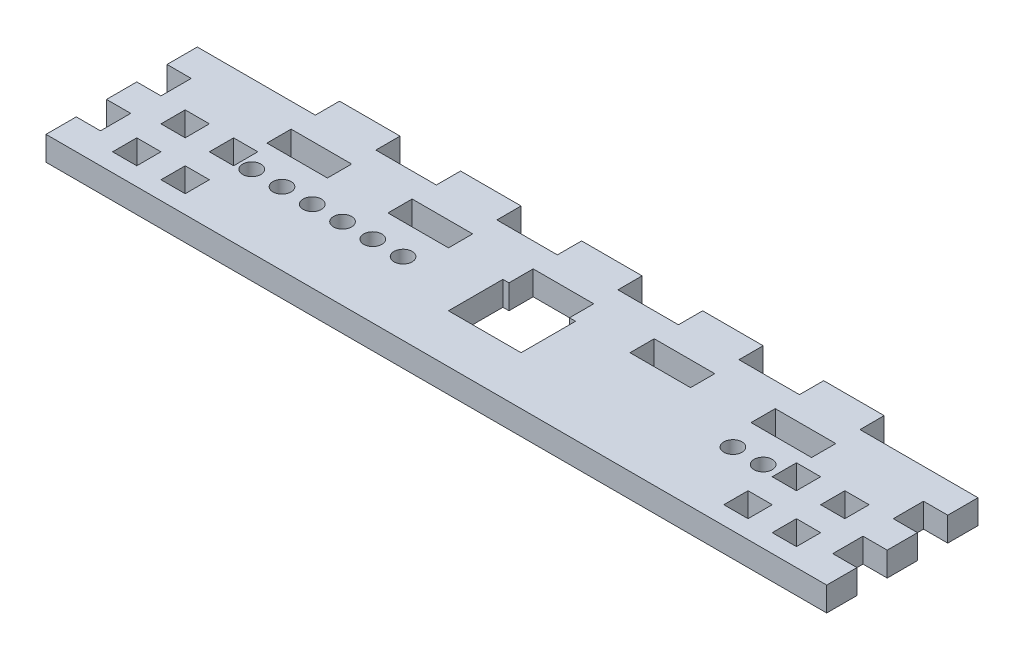
SolidWorks part; units mm, degrees
material "Maple"
ref_plane "Front Plane" through (0, 0, 0) normal (0, 0, 1) x (1, 0, 0)
ref_plane "Top Plane" through (0, 0, 0) normal (0, 1, 0) x (1, 0, 0)
ref_plane "Right Plane" through (0, 0, 0) normal (1, 0, 0) x (0, 0, -1)
sketch "Sketch1" plane through (0, 0, 0) normal (0, 1, 0) x (1, 0, 0)
  line L1 (0, 0) -> (121, 0)
  line L2 (0, 0) -> (0, -25)
  line L3 (0, -25) -> (121, -25)
  line L4 (121, 0) -> (121, -25)
  dimension "D1" = 121
  dimension "D2" = 25
extrude "Boss-Extrude1" add sketch "Sketch1" along normal blind 4
sketch "Sketch2" plane through (0, 0, 0) normal (0, -1, 0) x (-1, 0, 0)
  line L0 (0, 0) -> (0, -25) construction
  line L1 (0, -25) -> (4, -25)
  line L2 (0, -25) -> (0, -20)
  line L3 (0, -20) -> (4, -20)
  line L4 (4, -25) -> (4, -20)
  line L5 (-121, -25) -> (-125, -25)
  line L6 (-121, -25) -> (-121, -20)
  line L7 (-121, -20) -> (-125, -20)
  line L8 (-125, -25) -> (-125, -20)
  line L9 (0, -25) -> (-121, -25) construction
  dimension "D1" = 4
  dimension "D2" = 5
extrude "Boss-Extrude2" add sketch "Sketch2" against normal through all
pattern_linear "LPattern1" count 3 spacing 10 along (0, 0, -1) of "Boss-Extrude2"
sketch "Sketch3" plane through (0, 0, 0) normal (0, -1, 0) x (-1, 0, 0)
  line L0 (-60.5, -25) -> (-60.5, 0) construction
  line L1 (4, -25) -> (-125, -25) construction
  line L2 (-125, 0) -> (4, 0) construction
  line L4 (-55.5, 4) -> (-65.5, 4)
  line L5 (-55.5, 4) -> (-55.5, 0)
  line L6 (-55.5, 0) -> (-65.5, 0)
  line L7 (-65.5, 4) -> (-65.5, 0)
  line L8 (-55.5, 4) -> (-65.5, 0) construction
  line L9 (-55.5, 0) -> (-65.5, 4) construction
  point P6 (-60.5, 2)
  dimension "D1" = 4
  dimension "D2" = 10
extrude "Boss-Extrude3" add sketch "Sketch3" against normal through all
pattern_linear "LPattern2" count 3 spacing 20 along (1, 0, 0) count 3 spacing 20 along (-1, 0, 0) of "Boss-Extrude3"
sketch "Sketch4" plane through (0, 0, 0) normal (0, -1, 0) x (1, 0, 0)
  line L0 (60.5, -4) -> (60.5, 25) construction
  line L1 (15.5, 8) -> (25.5, 8)
  line L2 (15.5, 8) -> (15.5, 4)
  line L3 (15.5, 4) -> (25.5, 4)
  line L4 (25.5, 8) -> (25.5, 4)
  line L5 (35.5, 8) -> (45.5, 8)
  line L6 (35.5, 8) -> (35.5, 4)
  line L7 (35.5, 4) -> (45.5, 4)
  line L8 (45.5, 8) -> (45.5, 4)
  line L9 (55.5, 8) -> (65.5, 8)
  line L10 (55.5, 8) -> (55.5, 4)
  line L11 (55.5, 4) -> (65.5, 4)
  line L12 (65.5, 8) -> (65.5, 4)
  line L13 (75.5, 8) -> (85.5, 8)
  line L14 (75.5, 8) -> (75.5, 4)
  line L15 (75.5, 4) -> (85.5, 4)
  line L16 (85.5, 8) -> (85.5, 4)
  line L17 (95.5, 8) -> (105.5, 8)
  line L18 (95.5, 8) -> (95.5, 4)
  line L19 (95.5, 4) -> (105.5, 4)
  line L20 (105.5, 8) -> (105.5, 4)
  line L21 (55.5, -4) -> (65.5, -4) construction
  line L22 (-4, 25) -> (125, 25) construction
  dimension "D2" = 4
  dimension "D3" = 10
  dimension "D4" = 5
  dimension "D5" = 10
  dimension "D6" = 10
  dimension "D7" = 10
  dimension "D8" = 10
  dimension "D1" = 17
extrude "Cut-Extrude1" cut sketch "Sketch4" against normal through all
sketch "Sketch5" plane through (0, 4, 0) normal (0, 1, 0) x (1, 0, 0)
  line L0 (60.5, -25) -> (60.5, 4) construction
  line L1 (-4, -25) -> (125, -25) construction
  line L2 (55.5, 4) -> (65.5, 4) construction
  line L3 (121, -10) -> (121, -5) construction
  line L4 (54.5, -8) -> (66.5, -8)
  line L5 (54.5, -8) -> (54.5, -17)
  line L6 (54.5, -17) -> (66.5, -17)
  line L7 (66.5, -8) -> (66.5, -17)
  line L8 (54.5, -8) -> (66.5, -17) construction
  line L9 (54.5, -17) -> (66.5, -8) construction
  line L10 (0, -5) -> (0, -10) construction
  line L11 (105.5, -8) -> (95.5, -8) construction
  line L13 (55.5, -4) -> (65.5, -4) construction
  circle A0 centre (97.5, -13) radius 1.5
  circle A1 centre (102.5, -13) radius 1.5
  circle A2 centre (43, -13) radius 1.5
  circle A3 centre (38, -13) radius 1.5
  circle A4 centre (33, -13) radius 1.5
  circle A5 centre (28, -13) radius 1.5
  circle A6 centre (23, -13) radius 1.5
  circle A7 centre (18, -13) radius 1.5
  point P6 (60.5, -12.5)
  dimension "D4" = 3
  dimension "D5" = 3
  dimension "D1" = 9
  dimension "D2" = 12
  dimension "D6" = 5
  dimension "D8" = 18.5
  dimension "D9" = 5
  dimension "D10" = 5
  dimension "D11" = 5
  dimension "D12" = 5
  dimension "D13" = 5
  dimension "D14" = 18
  dimension "D7" = 5
  dimension "D3" = 4
extrude "Cut-Extrude2" cut sketch "Sketch5" against normal through all
sketch "Sketch6" [suppressed] plane through (0, 0, 0) normal (0, -1, 0) x (1, 0, 0)
  line L0 (45.5, 8) -> (35.5, 8) construction
  line L1 (-4, 13) -> (125, 13) construction
  line L2 (-4, 15) -> (-4, 10) construction
  line L3 (125, 10) -> (125, 15) construction
  circle A0 centre (38, 13) radius 1.5
  circle A1 centre (33, 13) radius 1.5
  circle A5 centre (28, 13) radius 1.5
  circle A6 centre (23, 13) radius 1.5
  circle A7 centre (18, 13) radius 1.5
  circle A9 centre (84, 13) radius 1.5
  circle A10 centre (89, 13) radius 1.5
  circle A11 centre (95.5, 13) radius 1.5
  circle A12 centre (100.5, 13) radius 1.5
  circle A13 centre (105.5, 13) radius 1.5
  dimension "D6" = 5
  dimension "D9" = 5
  dimension "D10" = 5
  dimension "D11" = 5
  dimension "D1" = 3
  dimension "D2" = 5
  dimension "D3" = 5
  dimension "D4" = 5
  dimension "D5" = 5
  dimension "D12" = 19.5
  dimension "D13" = 36
  dimension "D7" = 22
extrude "Cut-Extrude3" [suppressed] cut sketch "Sketch6" against normal through all
sketch "Sketch7" plane through (0, 0, 0) normal (0, -1, 0) x (1, 0, 0)
  line L0 (-4, 25) -> (125, 25) construction
  line L1 (4, 22) -> (8, 22)
  line L2 (4, 22) -> (4, 18)
  line L3 (4, 18) -> (8, 18)
  line L4 (8, 22) -> (8, 18)
  line L5 (12, 22) -> (16, 22)
  line L6 (12, 22) -> (12, 18)
  line L7 (12, 18) -> (16, 18)
  line L8 (16, 22) -> (16, 18)
  line L9 (4, 14) -> (8, 14)
  line L10 (4, 14) -> (4, 10)
  line L11 (4, 10) -> (8, 10)
  line L12 (8, 14) -> (8, 10)
  line L13 (12, 14) -> (16, 14)
  line L14 (12, 14) -> (12, 10)
  line L15 (12, 10) -> (16, 10)
  line L16 (16, 14) -> (16, 10)
  line L17 (105, 22) -> (109, 22)
  line L18 (105, 22) -> (105, 18)
  line L19 (105, 18) -> (109, 18)
  line L20 (109, 22) -> (109, 18)
  line L21 (105, 14) -> (109, 14)
  line L22 (105, 14) -> (105, 10)
  line L23 (105, 10) -> (109, 10)
  line L24 (109, 14) -> (109, 10)
  line L25 (113, 22) -> (117, 22)
  line L26 (113, 22) -> (113, 18)
  line L27 (113, 18) -> (117, 18)
  line L28 (117, 22) -> (117, 18)
  line L29 (113, 14) -> (117, 14)
  line L30 (113, 14) -> (113, 10)
  line L31 (113, 10) -> (117, 10)
  line L32 (117, 14) -> (117, 10)
  line L33 (-4, 25) -> (-4, 20) construction
  line L34 (125, 20) -> (125, 25) construction
  dimension "D1" = 3
  dimension "D2" = 8
  dimension "D3" = 4
  dimension "D4" = 4
  dimension "D5" = 4
  dimension "D6" = 4
  dimension "D7" = 4
  dimension "D8" = 8
  dimension "D9" = 4
  dimension "D10" = 4
  dimension "D11" = 4
extrude "Cut-Extrude4" cut sketch "Sketch7" against normal through all
equation "\"D5@Sketch5\"=\"D4@Sketch5\""
equation "\"D10@Sketch5\"=\"D9@Sketch5\""
equation "\"D11@Sketch5\"=\"D9@Sketch5\""
equation "\"D12@Sketch5\"=\"D9@Sketch5\""
equation "\"D13@Sketch5\"=\"D9@Sketch5\""
equation "\"D6@Sketch4\"=\"D5@Sketch4\""
equation "\"D7@Sketch4\"=\"D5@Sketch4\""
equation "\"D8@Sketch4\"=\"D5@Sketch4\""
equation "\"D5@Sketch6\"=\"D3@Sketch6\""
equation "\"D4@Sketch6\"=\"D3@Sketch6\""
equation "\"D6@Sketch6\"=\"D3@Sketch6\""
equation "\"D9@Sketch6\"=\"D3@Sketch6\""
equation "\"D10@Sketch6\"=\"D3@Sketch6\""
equation "\"D11@Sketch6\"=\"D3@Sketch6\""
